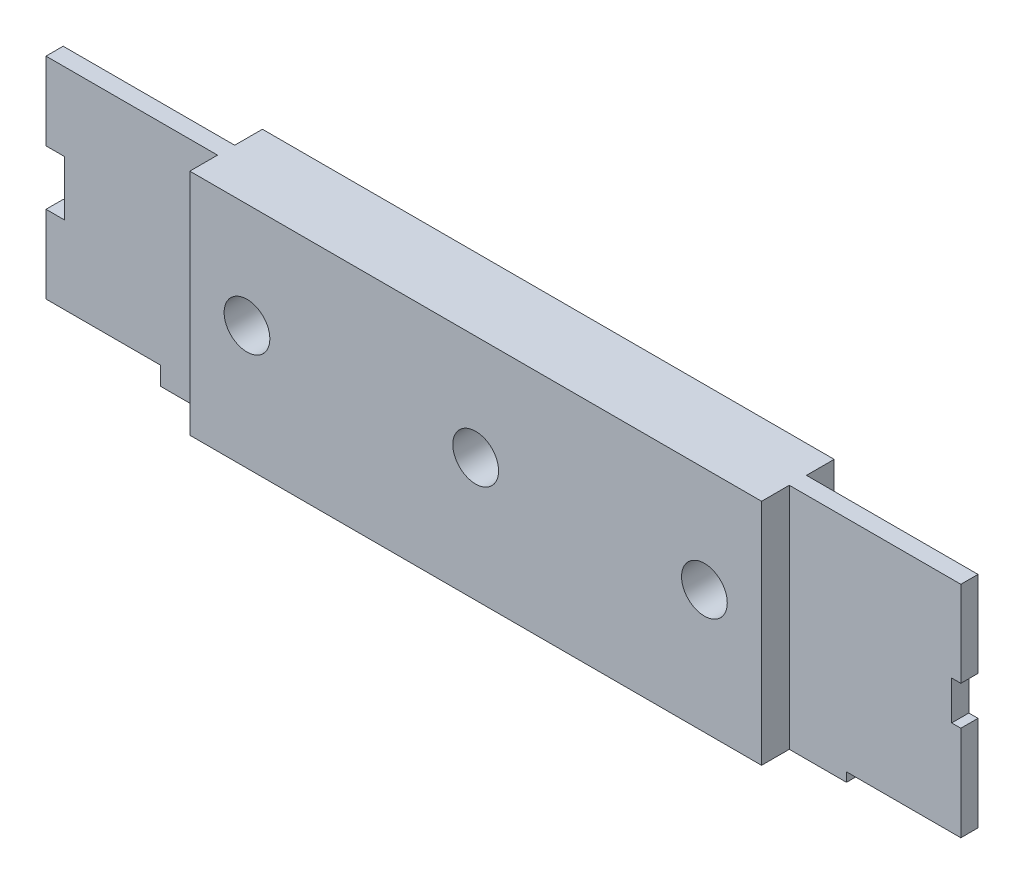
SolidWorks part; units mm, degrees
ref_plane "Alzado" through (0, 0, 0) normal (0, 0, 1) x (1, 0, 0)
ref_plane "Planta" through (0, 0, 0) normal (0, 1, 0) x (1, 0, 0)
ref_plane "Vista lateral" through (0, 0, 0) normal (1, 0, 0) x (0, 0, -1)
sketch "Croquis1" plane through (0, 0, 0) normal (0, 0, 1) x (1, 0, 0)
  line L0 (-40, 9.2) -> (40, 9.2)
  line L1 (40, 9.2) -> (40, 1.7)
  line L2 (40, 1.7) -> (39.2, 1.7)
  line L3 (39.2, 1.7) -> (39.2, -1.7)
  line L4 (39.2, -1.7) -> (40, -1.7)
  line L5 (40, -1.7) -> (40, -10)
  line L6 (40, -10) -> (30, -10)
  line L7 (30, -10) -> (30, -10.8)
  line L8 (30, -10.8) -> (-30, -10.8)
  line L9 (-30, -10.8) -> (-30, -9.2)
  line L10 (-30, -9.2) -> (-40, -9.2)
  line L11 (-40, -9.2) -> (-40, -2.4)
  line L12 (-40, -2.4) -> (-38.4, -2.4)
  line L13 (-38.4, -2.4) -> (-38.4, 2.4)
  line L14 (-38.4, 2.4) -> (-40, 2.4)
  line L15 (-40, 2.4) -> (-40, 9.2)
  line L16 (39.2, 0) -> (-38.4, 0) construction
  circle A0 centre (20, 0) radius 2
  circle A1 centre (0, 0) radius 2
  circle A2 centre (-20, 0) radius 2
  point P16 (-38.4, 0)
  point P18 (39.2, 0)
  point P19 (0, 9.2)
  dimension "D9" = 4
  dimension "D10" = 20
  dimension "D11" = 20
  dimension "D12" = 20
  dimension "D1" = 80
  dimension "D2" = 10
  dimension "D3" = 10
  dimension "D4" = 20
  dimension "D5" = 4.8
  dimension "D6" = 3.4
  dimension "D7" = 1.6
  dimension "D8" = 0.8
extrude "Saliente-Extruir1" add sketch "Croquis1" along normal mid plane 1.5
sketch "Croquis2" plane through (0, 0, 0) normal (0, 0, 1) x (1, 0, 0)
  line L0 (40, 9.2) -> (-40, 9.2) construction
  line L1 (-25, 9.2) -> (25, 9.2)
  line L2 (-25, 9.2) -> (-25, -10.8)
  line L3 (-25, -10.8) -> (25, -10.8)
  line L4 (25, 9.2) -> (25, -10.8)
  line L5 (-30, -10.8) -> (30, -10.8) construction
  line L6 (-40, 9.2) -> (-40, 2.4) construction
  line L7 (40, 1.7) -> (40, 9.2) construction
  circle A0 centre (-20, 0) radius 2
  circle A1 centre (0, 0) radius 2
  circle A2 centre (20, 0) radius 2
  dimension "D1" = 15
  dimension "D2" = 15
extrude "Saliente-Extruir2" add sketch "Croquis2" along normal mid plane 6.35
